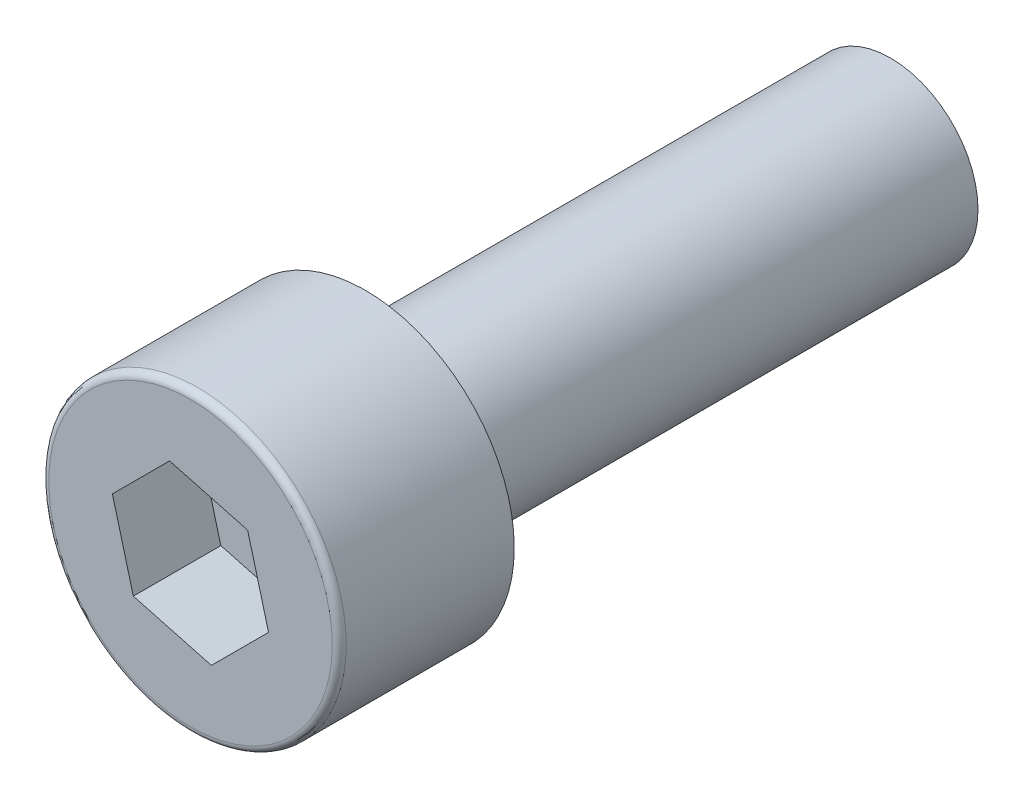
SolidWorks part; units mm, degrees
ref_plane "前视基准面" through (0, 0, 0) normal (0, 0, 1) x (1, 0, 0)
ref_plane "上视基准面" through (0, 0, 0) normal (0, 1, 0) x (1, 0, 0)
ref_plane "右视基准面" through (0, 0, 0) normal (1, 0, 0) x (0, 0, -1)
sketch "草图1" plane through (0, 0, 0) normal (0, 0, 1) x (1, 0, 0)
  circle A0 centre (0, 0) radius 4.25
  dimension "D1" = 8.5
extrude "凸台-拉伸1" add sketch "草图1" along normal blind 5
sketch "草图2" plane through (0, 0, 5) normal (0, 0, 1) x (1, 0, 0)
  line L1 (-1.633, -1.633) -> (0.5977, -2.2307)
  line L2 (0.5977, -2.2307) -> (2.2307, -0.5977)
  line L3 (2.2307, -0.5977) -> (1.633, 1.633)
  line L4 (1.633, 1.633) -> (-0.5977, 2.2307)
  line L5 (-0.5977, 2.2307) -> (-2.2307, 0.5977)
  line L6 (-2.2307, 0.5977) -> (-1.633, -1.633)
  circle A0 centre (0, 0) radius 2 construction
  dimension "D1" = 4
extrude "切除-拉伸1" cut sketch "草图2" against normal blind 2.5
sketch "草图3" plane through (0, 0, 0) normal (0, 0, -1) x (-1, 0, 0)
  circle A0 centre (0, 0) radius 2.5
  dimension "D1" = 5
extrude "凸台-拉伸2" add sketch "草图3" along normal blind 15
fillet "圆角1" radius 0.2 1 edges at (4.25, 0, 5)
